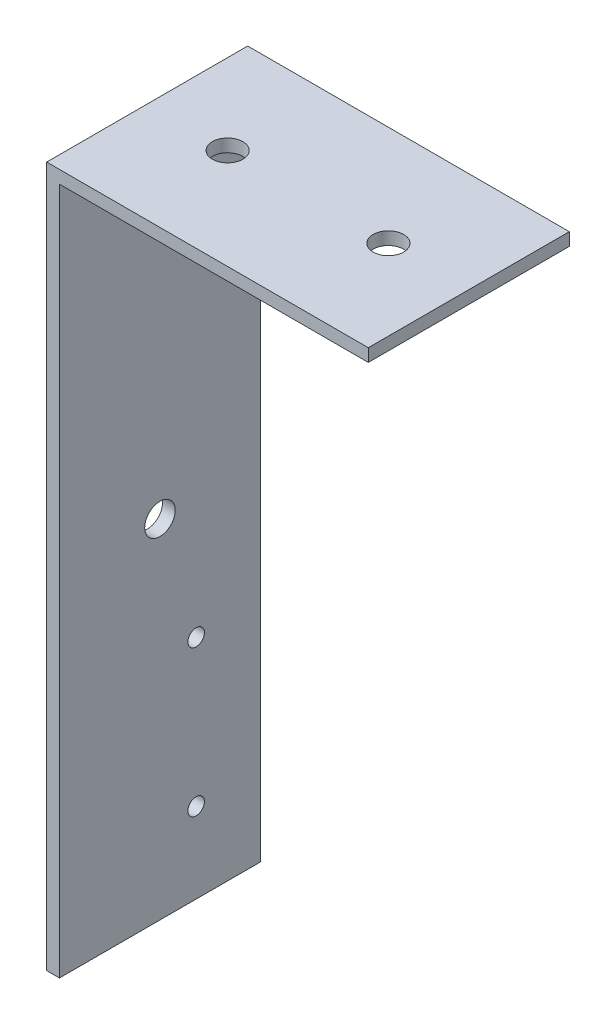
SolidWorks part; units mm, degrees
ref_plane "Front Plane" through (0, 0, 0) normal (0, 0, 1) x (1, 0, 0)
ref_plane "Top Plane" through (0, 0, 0) normal (0, 1, 0) x (1, 0, 0)
ref_plane "Right Plane" through (0, 0, 0) normal (1, 0, 0) x (0, 0, -1)
sketch "Sketch2" plane through (0, 0, 0) normal (0, 0, 1) x (1, 0, 0)
  line L0 (0, 0) -> (0, 87.1)
  line L1 (0, 87.1) -> (40, 87.1)
  line L2 (1.5875, 0) -> (1.5875, 85.5125)
  line L3 (1.5875, 85.5125) -> (40, 85.5125)
  line L4 (40, 87.1) -> (40, 85.5125)
  line L5 (0, 0) -> (1.5875, 0)
  dimension "D1" = 40
  dimension "D2" = 87.1
  dimension "D3" = 1.5875
extrude "Boss-Extrude1" add sketch "Sketch2" along normal blind 25
hole_wizard "#6 Clearance Hole1" positions "Sketch4" profile "Sketch3" hole size "#6" standard "ANSI Inch" end condition through all
sketch "Sketch4" plane through (0, 87.1, 0) normal (0, 1, 0) x (1, 0, 0)
  line L0 (40, 0) -> (0, 0) construction
  line L1 (0, -25) -> (0, 0) construction
  point P0 (10, -12.5)
  point P2 (30, -12.5)
  dimension "D1" = 12.5
  dimension "D2" = 10
  dimension "D3" = 20
sketch "Sketch3" plane through (10, 87.1, 12.5) normal (1, 0, 0) x (0, 0, 1)
  line L0 (0, 0) -> (0, 87.1)
  line L1 (0, 87.1) -> (1.8986, 87.1)
  line L2 (1.8986, 87.1) -> (1.8986, 0)
  line L5 (1.8986, 0) -> (0, 0)
  line L11 (0, -6.35) -> (0, 107.95) construction
  dimension "Thru Hole Dia." = 3.7973
  dimension "Thru Hole Depth" = 87.1
hole_wizard "#1 Clearance Hole2" positions "Sketch8" profile "Sketch7" hole size "#1" standard "ANSI Inch" end condition through all
sketch "Sketch8" plane through (0, 0, 0) normal (-1, 0, 0) x (0, 0, 1)
  line L0 (25, 0) -> (0, 0) construction
  line L2 (0, 0) -> (0, 85.5125) construction
  point P0 (8, 10)
  point P2 (8, 28.2)
  dimension "D1" = 10
  dimension "D2" = 8
  dimension "D3" = 18.2
sketch "Sketch7" plane through (0, 10, 8) normal (0, 1, 0) x (0, 0, 1)
  line L0 (0, 0) -> (0, 40)
  line L1 (0, 40) -> (1.0287, 40)
  line L2 (1.0287, 40) -> (1.0287, 0)
  line L5 (1.0287, 0) -> (0, 0)
  line L11 (0, -6.35) -> (0, 107.95) construction
  dimension "Thru Hole Dia." = 2.0574
  dimension "Thru Hole Depth" = 40
hole_wizard "#6 Clearance Hole2" positions "Sketch10" profile "Sketch9" hole size "#6" standard "ANSI Inch" end condition through all
sketch "Sketch10" plane through (0, 0, 0) normal (-1, 0, 0) x (0, 0, 1)
  line L0 (0, 87.1) -> (0, 0) construction
  circle A0 centre (8, 28.2) radius 1.0287 construction
  point P0 (12.5, 43.2)
  dimension "D1" = 15
  dimension "D2" = 12.5
sketch "Sketch9" plane through (0, 43.2, 12.5) normal (0, 1, 0) x (0, 0, 1)
  line L0 (0, 0) -> (0, 40)
  line L1 (0, 40) -> (1.8986, 40)
  line L2 (1.8986, 40) -> (1.8986, 0)
  line L5 (1.8986, 0) -> (0, 0)
  line L11 (0, -6.35) -> (0, 107.95) construction
  dimension "Thru Hole Dia." = 3.7973
  dimension "Thru Hole Depth" = 40
